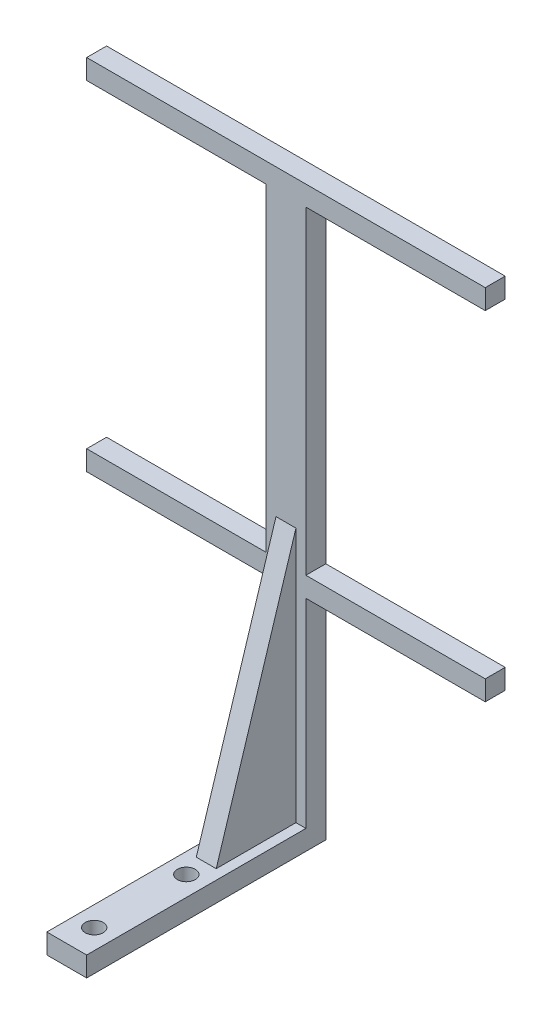
SolidWorks part; units mm, degrees
ref_plane "Front Plane" through (0, 0, 0) normal (0, 0, 1) x (1, 0, 0)
ref_plane "Top Plane" through (0, 0, 0) normal (0, 1, 0) x (1, 0, 0)
ref_plane "Right Plane" through (0, 0, 0) normal (1, 0, 0) x (0, 0, -1)
sketch "Sketch1" plane through (0, 0, 0) normal (0, 1, 0) x (1, 0, 0)
  line L1 (-5, 30) -> (5, 30)
  line L2 (-5, 30) -> (-5, -30)
  line L3 (-5, -30) -> (5, -30)
  line L4 (5, 30) -> (5, -30)
  line L5 (-5, 30) -> (5, -30) construction
  line L6 (-5, -30) -> (5, 30) construction
  point P0 (0, 0)
  dimension "D1" = 10
  dimension "D2" = 60
extrude "Boss-Extrude1" add sketch "Sketch1" along normal blind 5
sketch "Sketch2" plane through (0, 5, 0) normal (0, 1, 0) x (1, 0, 0)
  line L0 (5, 30) -> (-5, 30) construction
  line L2 (-5, 30) -> (-5, 25)
  line L3 (-5, 25) -> (5, 25)
  line L4 (5, 30) -> (5, 25)
  line L5 (0, 30) -> (5, 25) construction
  line L6 (-5, 25) -> (0, 30) construction
  line L7 (5, -30) -> (5, 30) construction
  line L8 (-5, 30) -> (5, 30)
  point P0 (0, 30)
  dimension "D2" = 5
extrude "Boss-Extrude2" add sketch "Sketch2" along normal blind 140
sketch "Sketch3" plane through (0, 0, 0) normal (1, 0, 0) x (0, 0, -1)
  line L0 (5, 5) -> (25, 69)
  line L1 (-30, 5) -> (25, 5) construction
  line L2 (25, 145) -> (25, 5) construction
  dimension "D1" = 20
  dimension "D2" = 64
rib "Rib1" sketch "Sketch3" sketch "Sketch3" thickness 5 extrusion direction parallel to sketch draft on no parameters "D1"=5
sketch "Sketch4" plane through (0, 0, -25) normal (0, 0, 1) x (1, 0, 0)
  line L0 (-5, 145) -> (5, 145) construction
  line L2 (-50, 145) -> (-50, 140)
  line L3 (-50, 140) -> (50, 140)
  line L4 (50, 145) -> (50, 140)
  line L5 (0, 145) -> (50, 140) construction
  line L6 (-50, 140) -> (0, 145) construction
  line L7 (-50, 145) -> (50, 145)
  line L8 (-50, 55) -> (50, 55)
  line L9 (-50, 60) -> (50, 60)
  line L10 (-50, 60) -> (-50, 55)
  line L11 (50, 60) -> (50, 55)
  point P0 (0, 145)
  dimension "D1" = 5
  dimension "D2" = 100
  dimension "D3" = 2
  dimension "D4" = 80
extrude "Boss-Extrude3" add sketch "Sketch4" against normal blind 5
sketch "Sketch6" plane through (0, 5, 0) normal (0, 1, 0) x (1, 0, 0)
  line L0 (0, -30) -> (0, 0) construction
  line L1 (-5, -30) -> (5, -30) construction
  circle A0 centre (0, 0) radius 2.25
  circle A1 centre (0, -23.1032) radius 2.25
  dimension "D1" = 4.5
  dimension "D2" = 4.5
extrude "Cut-Extrude1" cut sketch "Sketch6" against normal through all both and the other way through all
